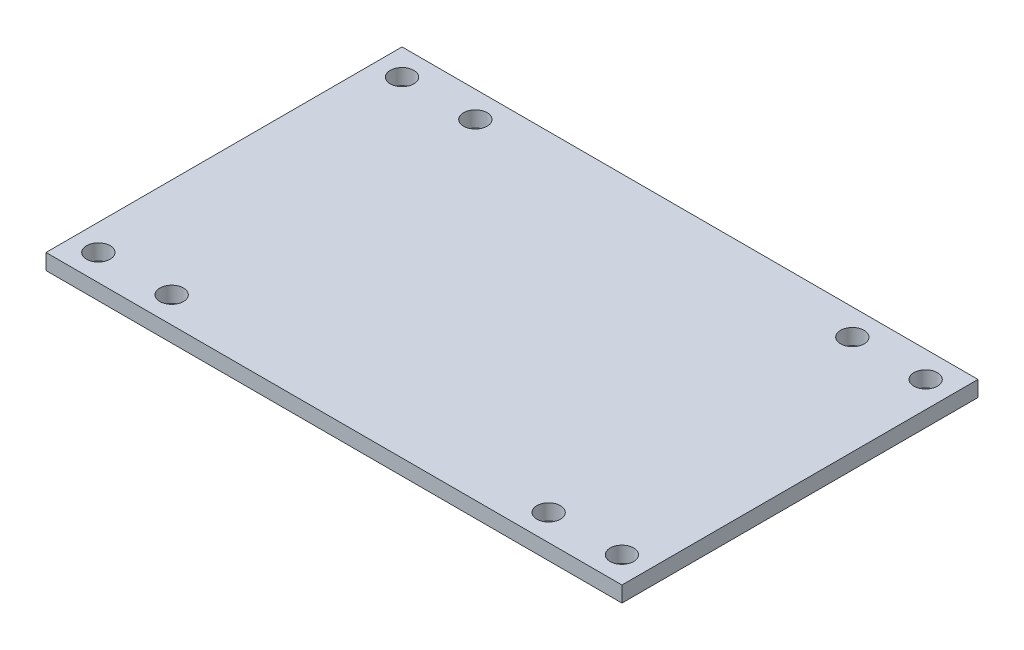
SolidWorks part; units mm, degrees
ref_plane "Front Plane" through (0, 0, 0) normal (0, 0, 1) x (1, 0, 0)
ref_plane "Top Plane" through (0, 0, 0) normal (0, 1, 0) x (1, 0, 0)
ref_plane "Right Plane" through (0, 0, 0) normal (1, 0, 0) x (0, 0, -1)
sketch "Sketch1" plane through (0, 0, 0) normal (0, 1, 0) x (1, 0, 0)
  line L1 (27.5, -17) -> (-27.5, -17)
  line L2 (27.5, -17) -> (27.5, 17)
  line L3 (27.5, 17) -> (-27.5, 17)
  line L4 (-27.5, -17) -> (-27.5, 17)
  line L5 (27.5, -17) -> (-27.5, 17) construction
  line L6 (27.5, 17) -> (-27.5, -17) construction
  point P0 (0, 0)
  dimension "D1" = 34
  dimension "D2" = 55
extrude "Boss-Extrude1" add sketch "Sketch1" along normal blind 1.5
sketch "Sketch3" plane through (0, 0, 0) normal (0, 1, 0) x (1, 0, 0)
  line L0 (18, -14.5) -> (18, 14.5) construction
  line L1 (-18, -14.5) -> (-18, 14.5) construction
  line L2 (-18, -14.5) -> (18, -14.5) construction
  line L3 (-18, 14.5) -> (18, 14.5) construction
  line L4 (27.5, -17) -> (-27.5, -17) construction
  line L5 (-27.5, -17) -> (-27.5, 17) construction
  line L6 (27.5, 17) -> (-27.5, 17) construction
  line L7 (27.5, -17) -> (27.5, 17) construction
  circle A4 centre (-18, 14.5) radius 1.125
  circle A5 centre (18, 14.5) radius 1.125
  circle A6 centre (-18, -14.5) radius 1.125
  circle A7 centre (18, -14.5) radius 1.125
  circle A8 centre (-25, 14.5) radius 1.125
  circle A9 centre (25, 14.5) radius 1.125
  circle A10 centre (25, -14.5) radius 1.125
  circle A11 centre (-25, -14.5) radius 1.125
  point P20 (0, -14.5)
  dimension "D2" = 29
  dimension "D3" = 2.5
  dimension "D4" = 2
  dimension "D5" = 2.25
  dimension "D6" = 2.25
  dimension "D7" = 2.25
  dimension "D8" = 2.25
  dimension "D9" = 2.5
  dimension "D10" = 36
  dimension "3.5/2" = 2.5
  dimension "D11" = 2
  dimension "D12" = 2.5
  dimension "D13" = 29
extrude "Cut-Extrude5" cut sketch "Sketch3" along normal through all
